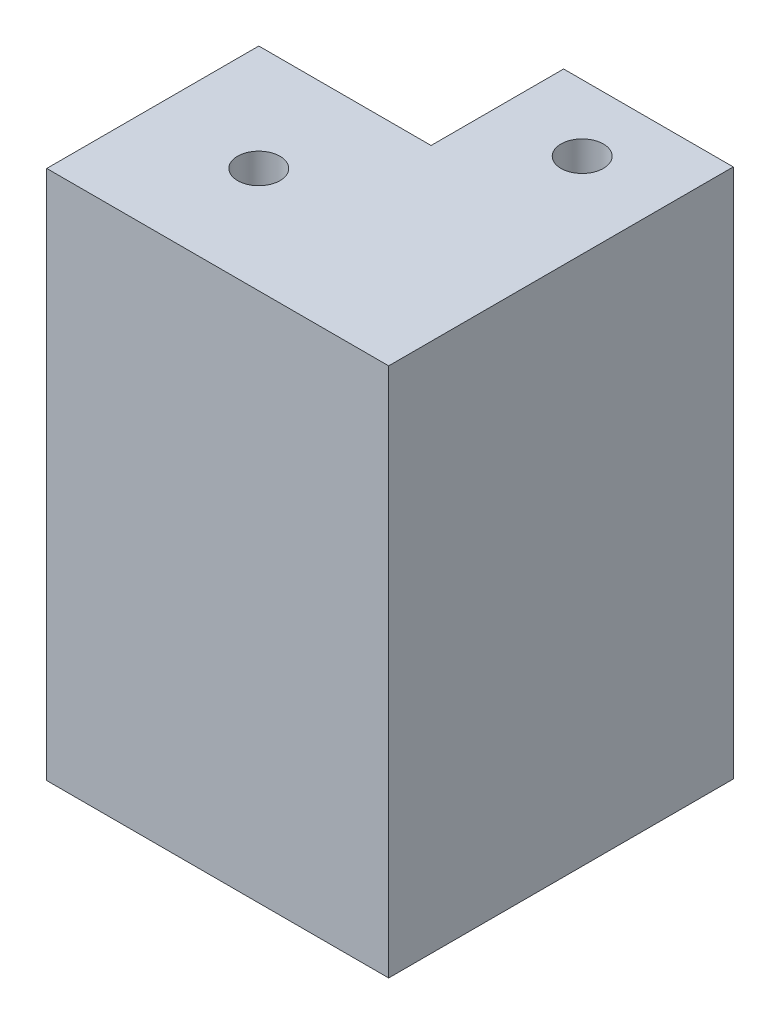
SolidWorks part; units mm, degrees
ref_plane "Front Plane" through (0, 0, 0) normal (0, 0, 1) x (1, 0, 0)
ref_plane "Top Plane" through (0, 0, 0) normal (0, 1, 0) x (1, 0, 0)
ref_plane "Right Plane" through (0, 0, 0) normal (1, 0, 0) x (0, 0, -1)
sketch "Sketch1" plane through (0, 0, 0) normal (0, 1, 0) x (1, 0, 0)
  line L19 (0, -40) -> (0, 0) construction
  line L24 (-25, 0) -> (0, -40) construction
  line L25 (0, 25) -> (-25, 25) construction
  line L26 (-25, 25) -> (-25, 0) construction
  line L27 (0, 25) -> (32, 0) construction
  line L28 (32, 0) -> (0, 0) construction
  line L29 (-32.5, 0) -> (0, 0)
  line L30 (-32.5, -40) -> (-32.5, 0)
  line L31 (32, -40) -> (-32.5, -40)
  line L32 (32, 25) -> (32, -40)
  line L33 (0, 25) -> (32, 25)
  line L34 (0, 0) -> (0, 25)
  circle A10 centre (-12.5, -20) radius 16 construction
  circle A11 centre (-12.5, -20) radius 6.75 construction
  circle A12 centre (16, 12.5) radius 6 construction
  circle A13 centre (16, 12.5) radius 11 construction
  circle A14 centre (-12.5, -20) radius 4
  circle A15 centre (16, 12.5) radius 4
  point P1 (0, 0)
  point P2 (0, 0)
  point P3 (36.3369, 30.2425)
  point P4 (0, 0)
  point P5 (0, 0)
  point P6 (0, 0)
  point P8 (0, 0)
  point P9 (0, 0)
  point P10 (0, 0)
  point P11 (0, 0)
  point P12 (16, 12.5)
  point P13 (-12.5, -13.2851)
  point P14 (0, 0)
  dimension "D4" = 40
  dimension "D6" = 8
  dimension "D3" = 32
  dimension "D5" = 20
  dimension "D7" = 13.5
  dimension "D8" = 32
  dimension "D9" = 8
  dimension "D10" = 12
  dimension "D11" = 22
  dimension "D1" = 25
  dimension "D2" = 25
extrude "Boss-Extrude1" add sketch "Sketch1" along normal blind 100
sketch "Sketch4" plane through (0, 0, 0) normal (0, -1, 0) x (-1, 0, 0)
  point P0 (12.5, -20)
hole_wizard "CBORE for M5 Hex Head Bolt2" positions "Sketch4" profile "Sketch5" counterbore size "M5" standard "ANSI Metric"
sketch "Sketch5" plane through (-12.5, 0, 20) normal (1, 0, 0) x (0, 0, -1)
  line L0 (0, 0) -> (0, 23.85)
  line L1 (0, 23.85) -> (6.75, 23.85)
  line L2 (6.75, 23.85) -> (6.75, 5)
  line L3 (6.75, 5) -> (16, 5)
  line L4 (16, 5) -> (16, 0)
  line L5 (16, 0) -> (0, 0)
  line L10 (0, 23.85) -> (-6.75, 23.85) construction
  line L11 (0, -6.35) -> (0, 107.95) construction
  dimension "Hole Dia." = 13.5
  dimension "Hole Depth" = 23.85
  dimension "C'Bore Dia." = 32
  dimension "C'Bore Depth" = 5
  dimension "Drill Angle" = 180
sketch "Sketch6" plane through (0, 0, 0) normal (0, -1, 0) x (-1, 0, 0)
  point P0 (-16, 12.5)
hole_wizard "CBORE for M5 Hex Head Bolt3" positions "Sketch6" profile "Sketch7" counterbore size "M5" standard "ANSI Metric"
sketch "Sketch7" plane through (16, 0, -12.5) normal (1, 0, 0) x (0, 0, -1)
  line L0 (0, 0) -> (0, 13.5)
  line L1 (0, 13.5) -> (5.1, 13.5)
  line L2 (5.1, 13.5) -> (5.1, 3.5)
  line L3 (5.1, 3.5) -> (11, 3.5)
  line L4 (11, 3.5) -> (11, 0)
  line L5 (11, 0) -> (0, 0)
  line L10 (0, 13.5) -> (-5.1, 13.5) construction
  line L11 (0, -6.35) -> (0, 107.95) construction
  dimension "Hole Dia." = 10.2
  dimension "Hole Depth" = 13.5
  dimension "C'Bore Dia." = 22
  dimension "C'Bore Depth" = 3.5
  dimension "Drill Angle" = 180
